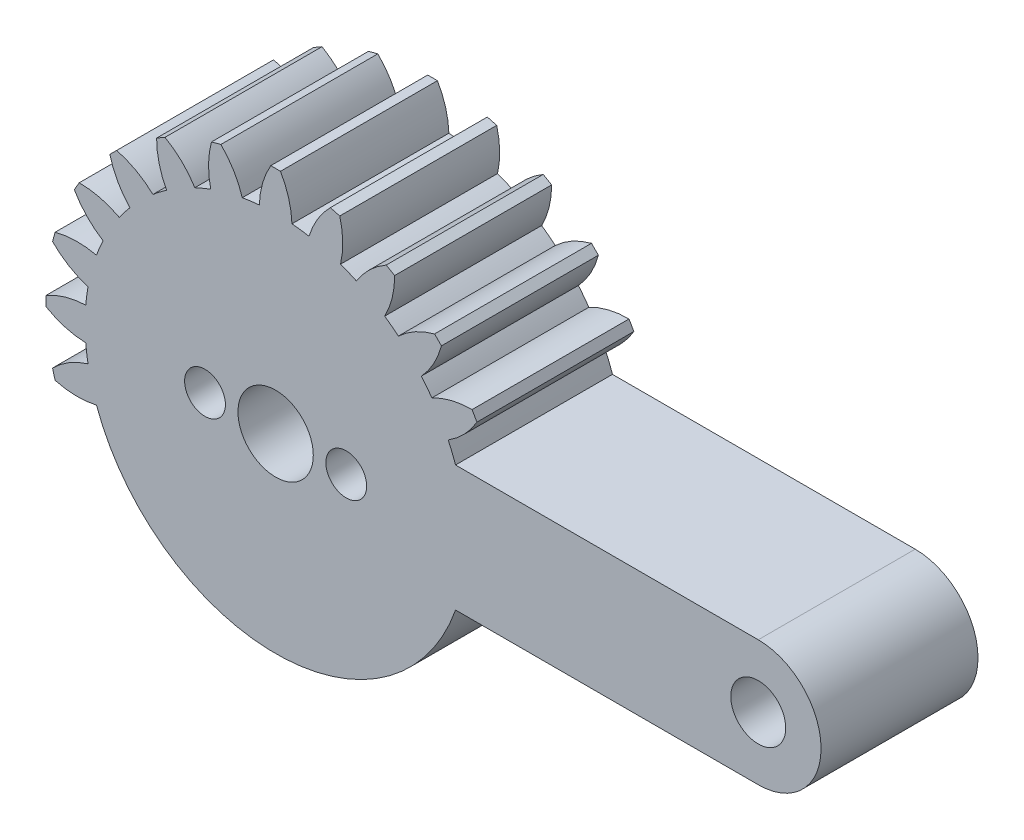
SolidWorks part; units mm, degrees
ref_plane "Front Plane" through (0, 0, 0) normal (0, 0, 1) x (1, 0, 0)
ref_plane "Top Plane" through (0, 0, 0) normal (0, 1, 0) x (1, 0, 0)
ref_plane "Right Plane" through (0, 0, 0) normal (1, 0, 0) x (0, 0, -1)
sketch "Sketch1" plane through (0, 0, 0) normal (0, 0, 1) x (1, 0, 0)
  line L0 (0, 0) -> (30.75, 0) construction
  line L1 (0, 14.63) -> (0, -14.63) construction
  line L2 (-0.31, 14.63) -> (0.31, 14.63)
  line L3 (3.4871, 14.2117) -> (4.086, 14.0513)
  line L4 (7.0465, 12.825) -> (7.5835, 12.515)
  line L5 (10.1258, 10.5642) -> (10.5642, 10.1258)
  line L6 (12.515, 7.5835) -> (12.825, 7.0465)
  line L7 (14.0513, 4.086) -> (14.2117, 3.4871)
  line L8 (14.63, 0.31) -> (14.63, -0.31)
  line L9 (14.2117, -3.4871) -> (14.0513, -4.086)
  line L10 (12.825, -7.0465) -> (12.515, -7.5835)
  line L11 (10.5642, -10.1258) -> (10.1258, -10.5642)
  line L12 (7.5835, -12.515) -> (7.0465, -12.825)
  line L13 (4.086, -14.0513) -> (3.4871, -14.2117)
  line L14 (0.31, -14.63) -> (-0.31, -14.63)
  line L15 (-3.4871, -14.2117) -> (-4.086, -14.0513)
  line L16 (-7.0465, -12.825) -> (-7.5835, -12.515)
  line L17 (-10.1258, -10.5642) -> (-10.5642, -10.1258)
  line L18 (-12.515, -7.5835) -> (-12.825, -7.0465)
  line L19 (-14.0513, -4.086) -> (-14.2117, -3.4871)
  line L20 (-14.63, -0.31) -> (-14.63, 0.31)
  line L21 (-14.2117, 3.4871) -> (-14.0513, 4.086)
  line L22 (-12.825, 7.0465) -> (-12.515, 7.5835)
  line L23 (-10.5642, 10.1258) -> (-10.1258, 10.5642)
  line L24 (-7.5835, 12.515) -> (-7.0465, 12.825)
  line L25 (-4.086, 14.0513) -> (-3.4871, 14.2117)
  line L26 (30.75, 4) -> (30.75, -6.3888) construction
  line L27 (30.75, 4) -> (11.4621, 4)
  line L28 (30.75, -4) -> (11.4621, -4)
  circle A0 centre (0, 0) radius 12.14
  arc A1 (30.75, -4) -> (30.75, 4) centre (30.75, 0) ccw
  circle A2 centre (0, 0) radius 1.75
  arc A3 (-1.04, 12.0954) -> (-0.31, 14.63) centre (4.3569, 11.9134) cw
  arc A4 (1.04, 12.0954) -> (0.31, 14.63) centre (-4.3569, 11.9134) ccw
  arc A5 (4.1351, 11.4141) -> (4.086, 14.0513) centre (-1.1251, 12.6352) ccw
  arc A6 (2.1259, 11.9524) -> (3.4871, 14.2117) centre (7.2919, 10.3798) cw
  arc A7 (6.9484, 9.9549) -> (7.5835, 12.515) centre (2.1835, 12.4958) ccw
  arc A8 (5.147, 10.9949) -> (7.0465, 12.825) centre (9.7299, 8.1389) cw
  arc A9 (9.2881, 7.8173) -> (10.5642, 10.1258) centre (5.3433, 11.5049) ccw
  arc A10 (7.8173, 9.2881) -> (10.1258, 10.5642) centre (11.5049, 5.3433) cw
  arc A11 (10.9949, 5.147) -> (12.825, 7.0465) centre (8.1389, 9.7299) ccw
  arc A12 (9.9549, 6.9484) -> (12.515, 7.5835) centre (12.4958, 2.1835) cw
  arc A13 (11.9524, 2.1259) -> (14.2117, 3.4871) centre (10.3798, 7.2919) ccw
  arc A14 (11.4141, 4.1351) -> (14.0513, 4.086) centre (12.6352, -1.1251) cw
  arc A15 (12.0954, -1.04) -> (14.63, -0.31) centre (11.9134, 4.3569) ccw
  arc A16 (12.0954, 1.04) -> (14.63, 0.31) centre (11.9134, -4.3569) cw
  arc A17 (11.4141, -4.1351) -> (14.0513, -4.086) centre (12.6352, 1.1251) ccw
  arc A18 (11.9524, -2.1259) -> (14.2117, -3.4871) centre (10.3798, -7.2919) cw
  arc A19 (9.9549, -6.9484) -> (12.515, -7.5835) centre (12.4958, -2.1835) ccw
  arc A20 (10.9949, -5.147) -> (12.825, -7.0465) centre (8.1389, -9.7299) cw
  arc A21 (7.8173, -9.2881) -> (10.1258, -10.5642) centre (11.5049, -5.3433) ccw
  arc A22 (9.2881, -7.8173) -> (10.5642, -10.1258) centre (5.3433, -11.5049) cw
  arc A23 (5.147, -10.9949) -> (7.0465, -12.825) centre (9.7299, -8.1389) ccw
  arc A24 (6.9484, -9.9549) -> (7.5835, -12.515) centre (2.1835, -12.4958) cw
  arc A25 (2.1259, -11.9524) -> (3.4871, -14.2117) centre (7.2919, -10.3798) ccw
  arc A26 (4.1351, -11.4141) -> (4.086, -14.0513) centre (-1.1251, -12.6352) cw
  arc A27 (-1.04, -12.0954) -> (-0.31, -14.63) centre (4.3569, -11.9134) ccw
  arc A28 (1.04, -12.0954) -> (0.31, -14.63) centre (-4.3569, -11.9134) cw
  arc A29 (-4.1351, -11.4141) -> (-4.086, -14.0513) centre (1.1251, -12.6352) ccw
  arc A30 (-2.1259, -11.9524) -> (-3.4871, -14.2117) centre (-7.2919, -10.3798) cw
  arc A31 (-6.9484, -9.9549) -> (-7.5835, -12.515) centre (-2.1835, -12.4958) ccw
  arc A32 (-5.147, -10.9949) -> (-7.0465, -12.825) centre (-9.7299, -8.1389) cw
  arc A33 (-9.2881, -7.8173) -> (-10.5642, -10.1258) centre (-5.3433, -11.5049) ccw
  arc A34 (-7.8173, -9.2881) -> (-10.1258, -10.5642) centre (-11.5049, -5.3433) cw
  arc A35 (-10.9949, -5.147) -> (-12.825, -7.0465) centre (-8.1389, -9.7299) ccw
  arc A36 (-9.9549, -6.9484) -> (-12.515, -7.5835) centre (-12.4958, -2.1835) cw
  arc A37 (-11.9524, -2.1259) -> (-14.2117, -3.4871) centre (-10.3798, -7.2919) ccw
  arc A38 (-11.4141, -4.1351) -> (-14.0513, -4.086) centre (-12.6352, 1.1251) cw
  arc A39 (-12.0954, 1.04) -> (-14.63, 0.31) centre (-11.9134, -4.3569) ccw
  arc A40 (-12.0954, -1.04) -> (-14.63, -0.31) centre (-11.9134, 4.3569) cw
  arc A41 (-11.4141, 4.1351) -> (-14.0513, 4.086) centre (-12.6352, -1.1251) ccw
  arc A42 (-11.9524, 2.1259) -> (-14.2117, 3.4871) centre (-10.3798, 7.2919) cw
  arc A43 (-9.9549, 6.9484) -> (-12.515, 7.5835) centre (-12.4958, 2.1835) ccw
  arc A44 (-10.9949, 5.147) -> (-12.825, 7.0465) centre (-8.1389, 9.7299) cw
  arc A45 (-7.8173, 9.2881) -> (-10.1258, 10.5642) centre (-11.5049, 5.3433) ccw
  arc A46 (-9.2881, 7.8173) -> (-10.5642, 10.1258) centre (-5.3433, 11.5049) cw
  arc A47 (-5.147, 10.9949) -> (-7.0465, 12.825) centre (-9.7299, 8.1389) ccw
  arc A48 (-6.9484, 9.9549) -> (-7.5835, 12.515) centre (-2.1835, 12.4958) cw
  arc A49 (-2.1259, 11.9524) -> (-3.4871, 14.2117) centre (-7.2919, 10.3798) ccw
  arc A50 (-4.1351, 11.4141) -> (-4.086, 14.0513) centre (1.1251, 12.6352) cw
  circle A51 centre (30.75, 0) radius 1.75
  point P155 (0, 0)
  dimension "D2" = 24.28
  dimension "D3" = 3.5
  dimension "D5" = 5.4
  dimension "D9" = 8
  dimension "D10" = 3.5
  dimension "D1" = 29.26
  dimension "D4" = 30.75
  dimension "D6" = 0.31
  dimension "D7" = 1.04
  dimension "D8" = 24
extrude "Boss-Extrude1" add sketch "Sketch1" along normal blind 10 contours A0 A18 L9 L28 A1 L27 L7 A13 A16 L8 A15 A51 | A0 | A0 A4 L2 A3 | A6 A0 A5 L3 | A8 A0 A7 L4 | A10 A0 A9 L5 | A12 A0 A11 L6 | A50 A0 A49 L25 | A48 A0 A47 L24 | A46 A0 A45 L23 | A44 A0 A43 L22 | A0 A13 L7 L27 | A16 A0 A15 L8 | A18 A0 L28 L9 | A42 A0 A41 L21 | A40 A0 A39 L20 | A38 A0 A37 L19
sketch "Sketch2" plane through (0, 0, 10) normal (0, 0, 1) x (1, 0, 0)
  line L0 (-4.5, 0) -> (4.5, 0) construction
  circle A0 centre (0, 0) radius 2.4
  circle A1 centre (-4.5, 0) radius 1.3
  circle A2 centre (4.5, 0) radius 1.3
  dimension "D1" = 2.6
  dimension "D2" = 2.6
  dimension "D3" = 4.8
  dimension "D4" = 9
extrude "Cut-Extrude1" cut sketch "Sketch2" against normal through all
